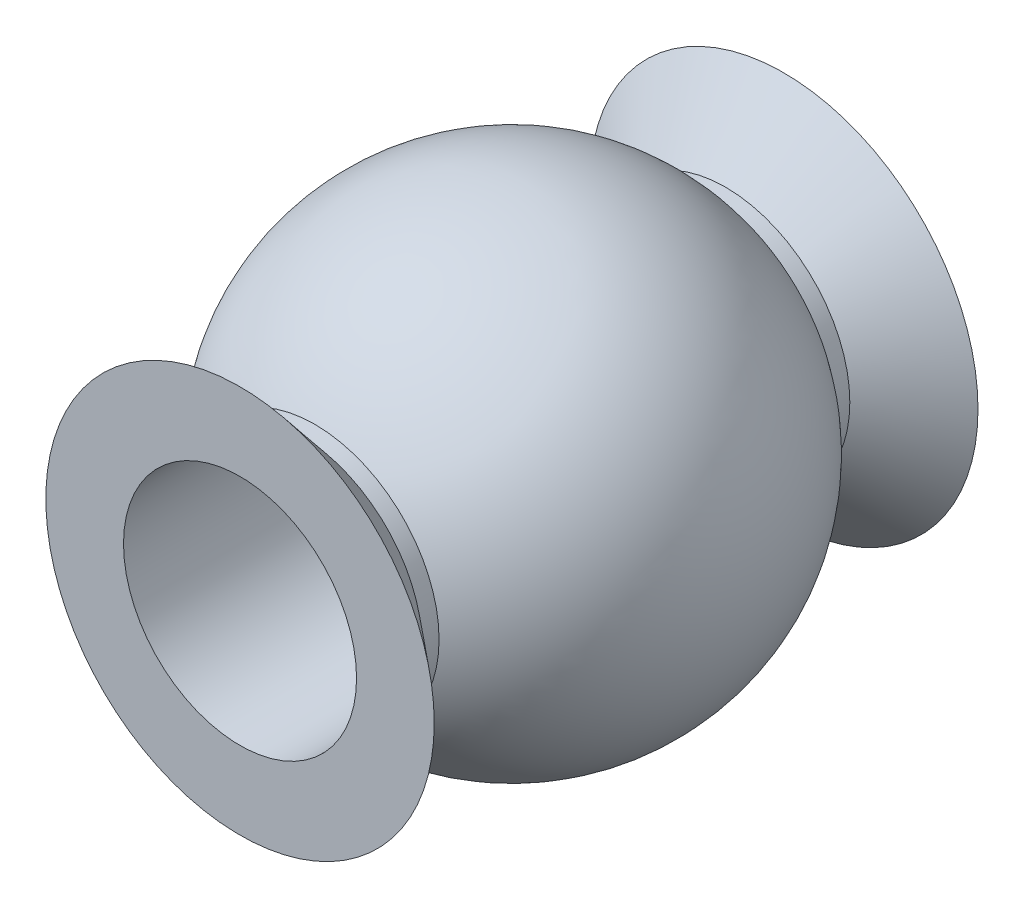
SolidWorks part; units mm, degrees
material "Zinc AC41A Alloy, As Cast"
ref_plane "Front Plane" through (0, 0, 0) normal (0, 0, 1) x (1, 0, 0)
ref_plane "Top Plane" through (0, 0, 0) normal (0, 1, 0) x (1, 0, 0)
ref_plane "Right Plane" through (0, 0, 0) normal (1, 0, 0) x (0, 0, -1)
sketch "Sketch1" plane through (0, 0, 0) normal (0, 1, 0) x (1, 0, 0)
  line L0 (0, 0) -> (0, 7)
  line L1 (0, 7) -> (2.5, 7)
  line L2 (2.5, 7) -> (1.6, 6.25)
  line L3 (1.6, 6.25) -> (1.6, 6.0377)
  line L4 (1.6, 0.75) -> (2.5, 0)
  line L5 (2.5, 0) -> (0, 0)
  line L6 (0, 3.5) -> (1.6, 3.5) construction
  line L7 (1.6, 0.9623) -> (1.6, 0.75)
  line L8 (1.6, 6.0377) -> (1.6, 0.9623) construction
  arc A0 (1.6, 0.9623) -> (1.6, 6.0377) centre (0, 3.5) ccw
  dimension "D1" = 6
  dimension "D2" = 7
  dimension "D3" = 2.5
  dimension "D4" = 1.6
  dimension "D5" = 5.5
  dimension "D6" = 0.75
revolve "Revolve1" add sketch "Sketch1" angle 360 about L0
sketch "Sketch2" plane through (0, 0, 0) normal (0, 0, 1) x (1, 0, 0)
  circle A0 centre (0, 0) radius 1.5
  dimension "D1" = 3
extrude "Cut-Extrude1" cut sketch "Sketch2" against normal through all
